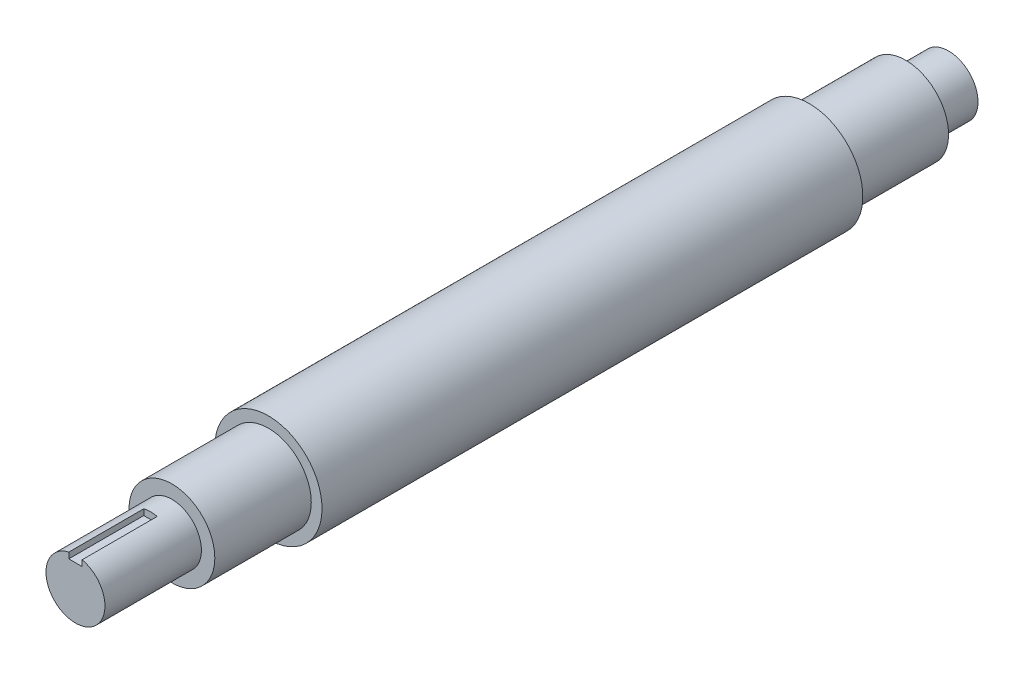
SolidWorks part; units mm, degrees
ref_plane "Front Plane" through (0, 0, 0) normal (0, 0, 1) x (1, 0, 0)
ref_plane "Top Plane" through (0, 0, 0) normal (0, 1, 0) x (1, 0, 0)
ref_plane "Right Plane" through (0, 0, 0) normal (1, 0, 0) x (0, 0, -1)
sketch "Sketch1" plane through (0, 0, 0) normal (0, 0, 1) x (1, 0, 0)
  line L0 (-105.6108, 0) -> (105.6108, 0) construction
  line L1 (0, -91.8487) -> (0, 91.8487) construction
  circle A0 centre (0, 0) radius 31.75
  point P4 (0, 0)
  point P8 (0, 0)
  dimension "D1" = 63.5
extrude "Boss-Extrude1" add sketch "Sketch1" along normal mid plane 320.3956
sketch "Sketch2" plane through (0, 0, 160.1978) normal (0, 0, 1) x (1, 0, 0)
  circle A0 centre (0, 0) radius 25.4
  dimension "D1" = 50.8
extrude "Boss-Extrude2" add sketch "Sketch2" along normal blind 57.15
sketch "Sketch3" plane through (0, 0, -160.1978) normal (0, 0, -1) x (-1, 0, 0)
  circle A0 centre (0, 0) radius 25.4
  dimension "D1" = 50.8
extrude "Boss-Extrude3" add sketch "Sketch3" along normal blind 57.15
sketch "Sketch5" plane through (0, 0, -217.3478) normal (0, 0, -1) x (-1, 0, 0)
  circle A0 centre (0, 0) radius 17.4625
  dimension "D1" = 34.925
extrude "Boss-Extrude5" add sketch "Sketch5" along normal blind 25.4
sketch "Sketch6" plane through (0, 0, 0) normal (1, 0, 0) x (0, 0, -1)
  line L0 (-255.2105, 0) -> (255.2105, 0) construction
  line L1 (0, -134.3892) -> (0, 134.3892) construction
  line L2 (-210.9978, -104.8827) -> (-210.9978, 104.8827) construction
  line L3 (210.9978, -92.5613) -> (210.9978, 92.5613) construction
  line L4 (-160.1978, 31.75) -> (-160.1978, -31.75) construction
  line L5 (160.1978, -31.75) -> (160.1978, 31.75) construction
  line L6 (153.8478, -84.4665) -> (153.8478, 84.4665) construction
  line L8 (-153.8478, -69.4558) -> (-153.8478, 69.4558) construction
  point P4 (0, 0)
  point P8 (0, 0)
  point P11 (-210.9978, 0)
  point P14 (210.9978, 0)
  point P21 (-149.225, 0)
  point P22 (153.8478, 0)
  point P24 (149.225, 0)
  point P27 (-153.8478, 0)
  dimension "D1" = 50.8
  dimension "D2" = 50.8
  dimension "D3" = 6.35
  dimension "D5" = 6.35
sketch "Sketch18" plane through (0, 0, 217.3478) normal (0, 0, 1) x (1, 0, 0)
  circle A0 centre (0, 0) radius 17.4625
  dimension "D1" = 34.925
extrude "Boss-Extrude6" add sketch "Sketch18" along normal blind 57.15
sketch "Sketch20" plane through (0, 0, 274.4978) normal (0, 0, 1) x (1, 0, 0)
  line L0 (-67.746, 0) -> (67.746, 0) construction
  line L1 (0, -47.1301) -> (0, 47.1301) construction
  line L3 (-3.9624, 13.5001) -> (3.9624, 13.5001)
  line L4 (-3.9624, 13.5001) -> (-3.9624, 21.4249)
  line L5 (-3.9624, 21.4249) -> (3.9624, 21.4249)
  line L6 (3.9624, 13.5001) -> (3.9624, 21.4249)
  line L7 (-3.9624, 13.5001) -> (3.9624, 21.4249) construction
  line L8 (-3.9624, 21.4249) -> (3.9624, 13.5001) construction
  circle A0 centre (0, 0) radius 17.4625 construction
  point P0 (0, 17.4625)
  point P5 (0, 0)
  point P9 (0, 0)
  dimension "D1" = 7.9248
  dimension "D2" = 7.9248
extrude "Cut-Extrude1" cut sketch "Sketch20" against normal blind 44.45
